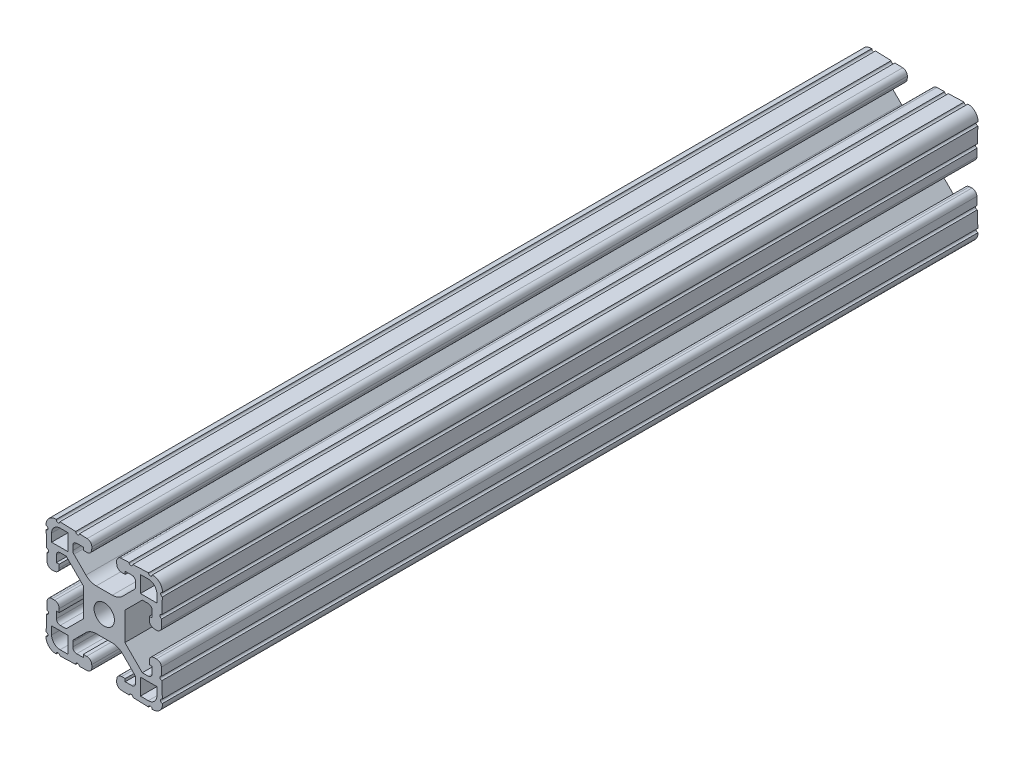
SolidWorks part; units mm, degrees
material "6061 Alloy"
ref_plane "Front Plane" through (0, 0, 0) normal (0, 0, 1) x (1, 0, 0)
ref_plane "Top Plane" through (0, 0, 0) normal (0, 1, 0) x (1, 0, 0)
ref_plane "Right Plane" through (0, 0, 0) normal (1, 0, 0) x (0, 0, -1)
sketch "Sketch1" plane through (0, 0, 0) normal (0, 0, 1) x (1, 0, 0)
  line L0 (0, 19.05) -> (-19.1669, 19.05) construction
  line L1 (-6.7564, 0) -> (-6.7564, 4.6011)
  line L2 (-8.7357, 18.8026) -> (-15.7642, 19.0481) construction
  line L3 (-17.655, 18.5041) -> (-4.0303, 18.0283) construction
  line L4 (-5.5829, 18.6925) -> (-5.7212, 14.7325) construction
  line L5 (-11.8364, 17.2212) -> (-11.8364, 11.8364)
  line L6 (-2.6337, 6.7564) -> (0, 6.7564)
  line L7 (0, 0) -> (0, 19.05) construction
  line L8 (0, 0) -> (-19.1669, 0) construction
  line L9 (1.0776, 1.0776) -> (-1.0776, -1.0776) construction
  line L10 (-5.9923, 8.1476) -> (-9.915, 12.0703)
  line L11 (-6.7564, 4.6011) -> (-12.4423, 10.287)
  line L12 (-11.8364, 11.8364) -> (-17.2212, 11.8364)
  line L13 (0, 0) -> (-19.1669, 19.1669) construction
  line L14 (-15.7642, 19.0481) -> (-5.5829, 18.6925)
  line L15 (-4.064, 17.0637) -> (-4.0924, 16.2514)
  line L17 (-19.0481, 15.7642) -> (-18.6925, 5.5829)
  line L19 (-17.2212, 11.8364) -> (-17.2212, 14.4272)
  line L20 (-11.8364, 17.2212) -> (-14.4272, 17.2212)
  line L21 (-10.287, 12.9683) -> (-10.287, 14.3745)
  line L22 (-14.3745, 10.287) -> (-12.4423, 10.287)
  line L23 (-9.017, 15.6445) -> (-6.858, 15.6445)
  line L24 (-6.858, 15.6445) -> (-6.858, 14.7325)
  line L25 (-5.7212, 14.7325) -> (-6.858, 14.7325)
  line L26 (-17.0637, 4.064) -> (-16.2514, 4.0924)
  line L27 (-14.7325, 5.7212) -> (-14.7325, 6.858)
  line L28 (-15.6445, 6.858) -> (-14.7325, 6.858)
  line L29 (-15.6445, 9.017) -> (-15.6445, 6.858)
  circle A0 centre (0, 0) radius 3.3274
  arc A5 (-15.7642, 19.0481) -> (-19.0481, 15.7642) centre (-15.875, 15.875) ccw
  arc A7 (-9.3449, 18.8239) -> (-8.1264, 18.7813) centre (-8.7357, 18.8026) ccw
  arc A10 (-17.2212, 14.4272) -> (-14.4272, 17.2212) centre (-14.4272, 14.4272) cw
  arc A11 (-4.0924, 16.2514) -> (-5.7212, 14.7325) centre (-5.6662, 16.3064) cw
  arc A12 (-5.5829, 18.6925) -> (-4.064, 17.0637) centre (-5.6378, 17.1187) cw
  arc A13 (-5.9923, 8.1476) -> (-2.6337, 6.7564) centre (-2.6337, 11.5062) ccw
  arc A14 (-9.915, 12.0703) -> (-10.287, 12.9683) centre (-9.017, 12.9683) cw
  arc A15 (-10.287, 14.3745) -> (-9.017, 15.6445) centre (-9.017, 14.3745) cw
  arc A16 (-15.6949, 19.0456) -> (-14.4764, 19.0031) centre (-15.0857, 19.0244) ccw
  arc A17 (-18.6925, 5.5829) -> (-17.0637, 4.064) centre (-17.1187, 5.6378) ccw
  arc A18 (-16.2514, 4.0924) -> (-14.7325, 5.7212) centre (-16.3064, 5.6662) ccw
  arc A19 (-14.3745, 10.287) -> (-15.6445, 9.017) centre (-14.3745, 9.017) ccw
  arc A20 (-18.8239, 9.3449) -> (-18.7813, 8.1264) centre (-18.8026, 8.7357) cw
  arc A21 (-19.0456, 15.6949) -> (-19.0031, 14.4764) centre (-19.0244, 15.0857) cw
  point P27 (-5.7298, 13.1063)
  point P49 (-4.009, 18.6376)
  point P55 (-10.287, 12.4423)
  dimension "D1" = 6.6548
  dimension "D10" = 3.175
  dimension "D13" = 2.794
  dimension "D7" = 1.5748
  dimension "D20" = 4.7498
  dimension "D21" = 1.27
  dimension "D3" = 13.5128
  dimension "D4" = 13.5128
  dimension "D8" = 3.048
  dimension "D6" = 38.1
  dimension "D9" = 2
  dimension "D2" = 38.1
  dimension "D11" = 19.05
  dimension "D5" = 20.574
  dimension "D14" = 7.2136
  dimension "D15" = 5.3848
  dimension "D16" = 3.9624
  dimension "D17" = 3.048
  dimension "D18" = 8.128
  dimension "D22" = 10.3124
  dimension "D23" = 3.9624
  dimension "D12" = 0.6096
  dimension "D19" = 13.716
sketch "Sketch3" plane through (0, 0, 0) normal (0, 0, 1) x (1, 0, 0)
  line L8 (-2.6337, 6.7564) -> (0, 6.7564) construction
  line L9 (-5.9923, 8.1476) -> (-9.915, 12.0703) construction
  line L10 (-10.287, 12.9683) -> (-10.287, 14.3745) construction
  line L11 (-9.017, 15.6445) -> (-6.858, 15.6445) construction
  line L12 (-6.858, 15.6445) -> (-6.858, 14.7325) construction
  line L13 (-5.7212, 14.7325) -> (-6.858, 14.7325) construction
  line L14 (-4.064, 17.0637) -> (-4.0924, 16.2514) construction
  line L15 (-15.7642, 19.0481) -> (-5.5829, 18.6925) construction
  line L16 (-19.0481, 15.7642) -> (-18.6925, 5.5829) construction
  line L17 (-17.0637, 4.064) -> (-16.2514, 4.0924) construction
  line L18 (-14.7325, 5.7212) -> (-14.7325, 6.858) construction
  line L19 (-15.6445, 6.858) -> (-14.7325, 6.858) construction
  line L20 (-15.6445, 9.017) -> (-15.6445, 6.858) construction
  line L21 (-14.3745, 10.287) -> (-12.4423, 10.287) construction
  line L22 (-6.7564, 4.6011) -> (-12.4423, 10.287) construction
  line L23 (-6.7564, 0) -> (-6.7564, 4.6011) construction
  line L24 (-2.6337, 6.7564) -> (2.6337, 6.7564)
  line L25 (-5.9923, 8.1476) -> (-9.915, 12.0703)
  line L26 (-10.287, 12.9683) -> (-10.287, 14.3745)
  line L27 (-9.017, 15.6445) -> (-6.858, 15.6445)
  line L28 (-6.858, 15.6445) -> (-6.858, 14.7325)
  line L29 (-5.7212, 14.7325) -> (-6.858, 14.7325)
  line L30 (-4.064, 17.0637) -> (-4.0924, 16.2514)
  line L31 (-15.7642, 19.0481) -> (-15.6949, 19.0456)
  line L32 (-19.0481, 15.7642) -> (-19.0456, 15.6949)
  line L33 (-17.0637, 4.064) -> (-16.2514, 4.0924)
  line L34 (-14.7325, 5.7212) -> (-14.7325, 6.858)
  line L35 (-15.6445, 6.858) -> (-14.7325, 6.858)
  line L36 (-15.6445, 9.017) -> (-15.6445, 6.858)
  line L37 (-14.3745, 10.287) -> (-12.4423, 10.287)
  line L38 (-6.7564, 4.6011) -> (-12.4423, 10.287)
  line L39 (-6.7564, -4.6011) -> (-6.7564, 4.6011)
  line L40 (0, 0) -> (-6.7564, 0) construction
  line L41 (0, 0) -> (0, 6.7564) construction
  line L42 (-8.1264, 18.7813) -> (-5.5829, 18.6925)
  line L43 (-14.4764, 19.0031) -> (-9.3449, 18.8239)
  line L48 (-11.8364, 11.8364) -> (-11.8364, 17.2212)
  line L49 (-17.2212, 11.8364) -> (-11.8364, 11.8364)
  line L50 (-17.2212, 14.4272) -> (-17.2212, 11.8364)
  line L51 (-11.8364, 17.2212) -> (-14.4272, 17.2212)
  line L52 (-19.0031, 14.4764) -> (-18.8239, 9.3449)
  line L53 (-18.7813, 8.1264) -> (-18.6925, 5.5829)
  line L54 (18.7813, 8.1264) -> (18.6925, 5.5829)
  line L55 (19.0031, 14.4764) -> (18.8239, 9.3449)
  line L56 (11.8364, 17.2212) -> (14.4272, 17.2212)
  line L57 (17.2212, 14.4272) -> (17.2212, 11.8364)
  line L58 (17.2212, 11.8364) -> (11.8364, 11.8364)
  line L59 (11.8364, 11.8364) -> (11.8364, 17.2212)
  line L60 (14.4764, 19.0031) -> (9.3449, 18.8239)
  line L61 (8.1264, 18.7813) -> (5.5829, 18.6925)
  line L62 (6.7564, -4.6011) -> (6.7564, 4.6011)
  line L63 (6.7564, 4.6011) -> (12.4423, 10.287)
  line L64 (14.3745, 10.287) -> (12.4423, 10.287)
  line L65 (15.6445, 9.017) -> (15.6445, 6.858)
  line L66 (15.6445, 6.858) -> (14.7325, 6.858)
  line L67 (14.7325, 5.7212) -> (14.7325, 6.858)
  line L68 (17.0637, 4.064) -> (16.2514, 4.0924)
  line L69 (19.0481, 15.7642) -> (19.0456, 15.6949)
  line L70 (15.7642, 19.0481) -> (15.6949, 19.0456)
  line L71 (4.064, 17.0637) -> (4.0924, 16.2514)
  line L72 (5.7212, 14.7325) -> (6.858, 14.7325)
  line L73 (6.858, 15.6445) -> (6.858, 14.7325)
  line L74 (9.017, 15.6445) -> (6.858, 15.6445)
  line L75 (10.287, 12.9683) -> (10.287, 14.3745)
  line L76 (5.9923, 8.1476) -> (9.915, 12.0703)
  line L77 (5.9923, -8.1476) -> (9.915, -12.0703)
  line L78 (10.287, -12.9683) -> (10.287, -14.3745)
  line L79 (9.017, -15.6445) -> (6.858, -15.6445)
  line L80 (6.858, -15.6445) -> (6.858, -14.7325)
  line L81 (5.7212, -14.7325) -> (6.858, -14.7325)
  line L82 (4.064, -17.0637) -> (4.0924, -16.2514)
  line L83 (15.7642, -19.0481) -> (15.6949, -19.0456)
  line L84 (19.0481, -15.7642) -> (19.0456, -15.6949)
  line L85 (17.0637, -4.064) -> (16.2514, -4.0924)
  line L86 (14.7325, -5.7212) -> (14.7325, -6.858)
  line L87 (15.6445, -6.858) -> (14.7325, -6.858)
  line L88 (15.6445, -9.017) -> (15.6445, -6.858)
  line L89 (14.3745, -10.287) -> (12.4423, -10.287)
  line L90 (6.7564, -4.6011) -> (12.4423, -10.287)
  line L91 (8.1264, -18.7813) -> (5.5829, -18.6925)
  line L92 (14.4764, -19.0031) -> (9.3449, -18.8239)
  line L93 (11.8364, -11.8364) -> (11.8364, -17.2212)
  line L94 (17.2212, -11.8364) -> (11.8364, -11.8364)
  line L95 (17.2212, -14.4272) -> (17.2212, -11.8364)
  line L96 (11.8364, -17.2212) -> (14.4272, -17.2212)
  line L97 (19.0031, -14.4764) -> (18.8239, -9.3449)
  line L98 (18.7813, -8.1264) -> (18.6925, -5.5829)
  line L99 (-18.7813, -8.1264) -> (-18.6925, -5.5829)
  line L100 (-19.0031, -14.4764) -> (-18.8239, -9.3449)
  line L101 (-11.8364, -17.2212) -> (-14.4272, -17.2212)
  line L102 (-17.2212, -14.4272) -> (-17.2212, -11.8364)
  line L103 (-17.2212, -11.8364) -> (-11.8364, -11.8364)
  line L104 (-11.8364, -11.8364) -> (-11.8364, -17.2212)
  line L105 (-14.4764, -19.0031) -> (-9.3449, -18.8239)
  line L106 (-8.1264, -18.7813) -> (-5.5829, -18.6925)
  line L107 (-6.7564, -4.6011) -> (-12.4423, -10.287)
  line L108 (-14.3745, -10.287) -> (-12.4423, -10.287)
  line L109 (-15.6445, -9.017) -> (-15.6445, -6.858)
  line L110 (-15.6445, -6.858) -> (-14.7325, -6.858)
  line L111 (-14.7325, -5.7212) -> (-14.7325, -6.858)
  line L112 (-17.0637, -4.064) -> (-16.2514, -4.0924)
  line L113 (-19.0481, -15.7642) -> (-19.0456, -15.6949)
  line L114 (-15.7642, -19.0481) -> (-15.6949, -19.0456)
  line L115 (-4.064, -17.0637) -> (-4.0924, -16.2514)
  line L116 (-5.7212, -14.7325) -> (-6.858, -14.7325)
  line L117 (-6.858, -15.6445) -> (-6.858, -14.7325)
  line L118 (-9.017, -15.6445) -> (-6.858, -15.6445)
  line L119 (-10.287, -12.9683) -> (-10.287, -14.3745)
  line L120 (-5.9923, -8.1476) -> (-9.915, -12.0703)
  line L121 (-2.6337, -6.7564) -> (2.6337, -6.7564)
  arc A9 (-15.6949, 19.0456) -> (-14.4764, 19.0031) centre (-15.0857, 19.0244) ccw construction
  arc A10 (-5.9923, 8.1476) -> (-2.6337, 6.7564) centre (-2.6337, 11.5062) ccw construction
  arc A11 (-10.287, 12.9683) -> (-9.915, 12.0703) centre (-9.017, 12.9683) ccw construction
  arc A12 (-9.017, 15.6445) -> (-10.287, 14.3745) centre (-9.017, 14.3745) ccw construction
  arc A13 (-5.7212, 14.7325) -> (-4.0924, 16.2514) centre (-5.6662, 16.3064) ccw construction
  arc A14 (-4.064, 17.0637) -> (-5.5829, 18.6925) centre (-5.6378, 17.1187) ccw construction
  arc A15 (-15.7642, 19.0481) -> (-19.0481, 15.7642) centre (-15.875, 15.875) ccw construction
  arc A16 (-18.6925, 5.5829) -> (-17.0637, 4.064) centre (-17.1187, 5.6378) ccw construction
  arc A17 (-16.2514, 4.0924) -> (-14.7325, 5.7212) centre (-16.3064, 5.6662) ccw construction
  arc A18 (-14.3745, 10.287) -> (-15.6445, 9.017) centre (-14.3745, 9.017) ccw construction
  arc A19 (-9.3449, 18.8239) -> (-8.1264, 18.7813) centre (-8.7357, 18.8026) ccw construction
  arc A20 (-18.7813, 8.1264) -> (-18.8239, 9.3449) centre (-18.8026, 8.7357) ccw construction
  arc A21 (-19.0031, 14.4764) -> (-19.0456, 15.6949) centre (-19.0244, 15.0857) ccw construction
  arc A22 (-15.6949, 19.0456) -> (-14.4764, 19.0031) centre (-15.0857, 19.0244) ccw
  arc A23 (-5.9923, 8.1476) -> (-2.6337, 6.7564) centre (-2.6337, 11.5062) ccw
  arc A24 (-10.287, 12.9683) -> (-9.915, 12.0703) centre (-9.017, 12.9683) ccw
  arc A25 (-9.017, 15.6445) -> (-10.287, 14.3745) centre (-9.017, 14.3745) ccw
  arc A26 (-5.7212, 14.7325) -> (-4.0924, 16.2514) centre (-5.6662, 16.3064) ccw
  arc A27 (-4.064, 17.0637) -> (-5.5829, 18.6925) centre (-5.6378, 17.1187) ccw
  arc A28 (-15.7642, 19.0481) -> (-19.0481, 15.7642) centre (-15.875, 15.875) ccw
  arc A29 (-18.6925, 5.5829) -> (-17.0637, 4.064) centre (-17.1187, 5.6378) ccw
  arc A30 (-16.2514, 4.0924) -> (-14.7325, 5.7212) centre (-16.3064, 5.6662) ccw
  arc A31 (-14.3745, 10.287) -> (-15.6445, 9.017) centre (-14.3745, 9.017) ccw
  arc A32 (-9.3449, 18.8239) -> (-8.1264, 18.7813) centre (-8.7357, 18.8026) ccw
  arc A33 (-18.7813, 8.1264) -> (-18.8239, 9.3449) centre (-18.8026, 8.7357) ccw
  arc A34 (-19.0031, 14.4764) -> (-19.0456, 15.6949) centre (-19.0244, 15.0857) ccw
  arc A35 (14.4272, 17.2212) -> (17.2212, 14.4272) centre (14.4272, 14.4272) cw
  circle A36 centre (0, 0) radius 3.3274
  circle A37 centre (0, 0) radius 3.3274
  arc A39 (-14.4272, 17.2212) -> (-17.2212, 14.4272) centre (-14.4272, 14.4272) ccw
  arc A40 (19.0031, 14.4764) -> (19.0456, 15.6949) centre (19.0244, 15.0857) cw
  arc A41 (18.7813, 8.1264) -> (18.8239, 9.3449) centre (18.8026, 8.7357) cw
  arc A42 (9.3449, 18.8239) -> (8.1264, 18.7813) centre (8.7357, 18.8026) cw
  arc A43 (14.3745, 10.287) -> (15.6445, 9.017) centre (14.3745, 9.017) cw
  arc A44 (16.2514, 4.0924) -> (14.7325, 5.7212) centre (16.3064, 5.6662) cw
  arc A45 (18.6925, 5.5829) -> (17.0637, 4.064) centre (17.1187, 5.6378) cw
  arc A46 (15.7642, 19.0481) -> (19.0481, 15.7642) centre (15.875, 15.875) cw
  arc A47 (4.064, 17.0637) -> (5.5829, 18.6925) centre (5.6378, 17.1187) cw
  arc A48 (5.7212, 14.7325) -> (4.0924, 16.2514) centre (5.6662, 16.3064) cw
  arc A49 (9.017, 15.6445) -> (10.287, 14.3745) centre (9.017, 14.3745) cw
  arc A50 (10.287, 12.9683) -> (9.915, 12.0703) centre (9.017, 12.9683) cw
  arc A51 (5.9923, 8.1476) -> (2.6337, 6.7564) centre (2.6337, 11.5062) cw
  arc A52 (15.6949, 19.0456) -> (14.4764, 19.0031) centre (15.0857, 19.0244) cw
  arc A54 (15.6949, -19.0456) -> (14.4764, -19.0031) centre (15.0857, -19.0244) ccw
  arc A55 (5.9923, -8.1476) -> (2.6337, -6.7564) centre (2.6337, -11.5062) ccw
  arc A56 (10.287, -12.9683) -> (9.915, -12.0703) centre (9.017, -12.9683) ccw
  arc A57 (9.017, -15.6445) -> (10.287, -14.3745) centre (9.017, -14.3745) ccw
  arc A58 (5.7212, -14.7325) -> (4.0924, -16.2514) centre (5.6662, -16.3064) ccw
  arc A59 (4.064, -17.0637) -> (5.5829, -18.6925) centre (5.6378, -17.1187) ccw
  arc A60 (15.7642, -19.0481) -> (19.0481, -15.7642) centre (15.875, -15.875) ccw
  arc A61 (18.6925, -5.5829) -> (17.0637, -4.064) centre (17.1187, -5.6378) ccw
  arc A62 (16.2514, -4.0924) -> (14.7325, -5.7212) centre (16.3064, -5.6662) ccw
  arc A63 (14.3745, -10.287) -> (15.6445, -9.017) centre (14.3745, -9.017) ccw
  arc A64 (9.3449, -18.8239) -> (8.1264, -18.7813) centre (8.7357, -18.8026) ccw
  arc A65 (18.7813, -8.1264) -> (18.8239, -9.3449) centre (18.8026, -8.7357) ccw
  arc A66 (19.0031, -14.4764) -> (19.0456, -15.6949) centre (19.0244, -15.0857) ccw
  arc A67 (-14.4272, -17.2212) -> (-17.2212, -14.4272) centre (-14.4272, -14.4272) cw
  arc A68 (14.4272, -17.2212) -> (17.2212, -14.4272) centre (14.4272, -14.4272) ccw
  arc A69 (-19.0031, -14.4764) -> (-19.0456, -15.6949) centre (-19.0244, -15.0857) cw
  arc A70 (-18.7813, -8.1264) -> (-18.8239, -9.3449) centre (-18.8026, -8.7357) cw
  arc A71 (-9.3449, -18.8239) -> (-8.1264, -18.7813) centre (-8.7357, -18.8026) cw
  arc A72 (-14.3745, -10.287) -> (-15.6445, -9.017) centre (-14.3745, -9.017) cw
  arc A73 (-16.2514, -4.0924) -> (-14.7325, -5.7212) centre (-16.3064, -5.6662) cw
  arc A74 (-18.6925, -5.5829) -> (-17.0637, -4.064) centre (-17.1187, -5.6378) cw
  arc A75 (-15.7642, -19.0481) -> (-19.0481, -15.7642) centre (-15.875, -15.875) cw
  arc A76 (-4.064, -17.0637) -> (-5.5829, -18.6925) centre (-5.6378, -17.1187) cw
  arc A77 (-5.7212, -14.7325) -> (-4.0924, -16.2514) centre (-5.6662, -16.3064) cw
  arc A78 (-9.017, -15.6445) -> (-10.287, -14.3745) centre (-9.017, -14.3745) cw
  arc A79 (-10.287, -12.9683) -> (-9.915, -12.0703) centre (-9.017, -12.9683) cw
  arc A80 (-5.9923, -8.1476) -> (-2.6337, -6.7564) centre (-2.6337, -11.5062) cw
  arc A81 (-15.6949, -19.0456) -> (-14.4764, -19.0031) centre (-15.0857, -19.0244) cw
  point P201 (6.7564, 0)
  dimension "D1" = 0
extrude "Extrude1" add sketch "Sketch3" along normal mid plane 266.7
ref_plane "Plane1" through (0, 19.0481, 0) normal (0, -1, 0) x (-1, 0, 0)
ref_plane "Plane2" through (19.0481, 0, 0) normal (-1, 0, 0) x (0, 0, 1)
ref_plane "Plane3" through (0, -19.0481, 0) normal (0, 1, 0) x (1, 0, 0)
ref_plane "Plane4" through (-19.0481, 0, 0) normal (1, 0, 0) x (0, 0, -1)
ref_plane "Plane5" through (0, 0, 0) normal (-1, 0, 0) x (0, 0, 1)
ref_plane "Plane6" through (0, 0, 0) normal (0, 1, 0) x (1, 0, 0)
equation "\"D11@Sketch1\" = \"D6@Sketch1\"/2"
equation "\"D16@Sketch1\" = \"D8@Sketch1\"*1.3"
equation "\"D17@Sketch1\" = \"D8@Sketch1\""
equation "\"D12@Sketch1\" = \"D8@Sketch1\"/5"
